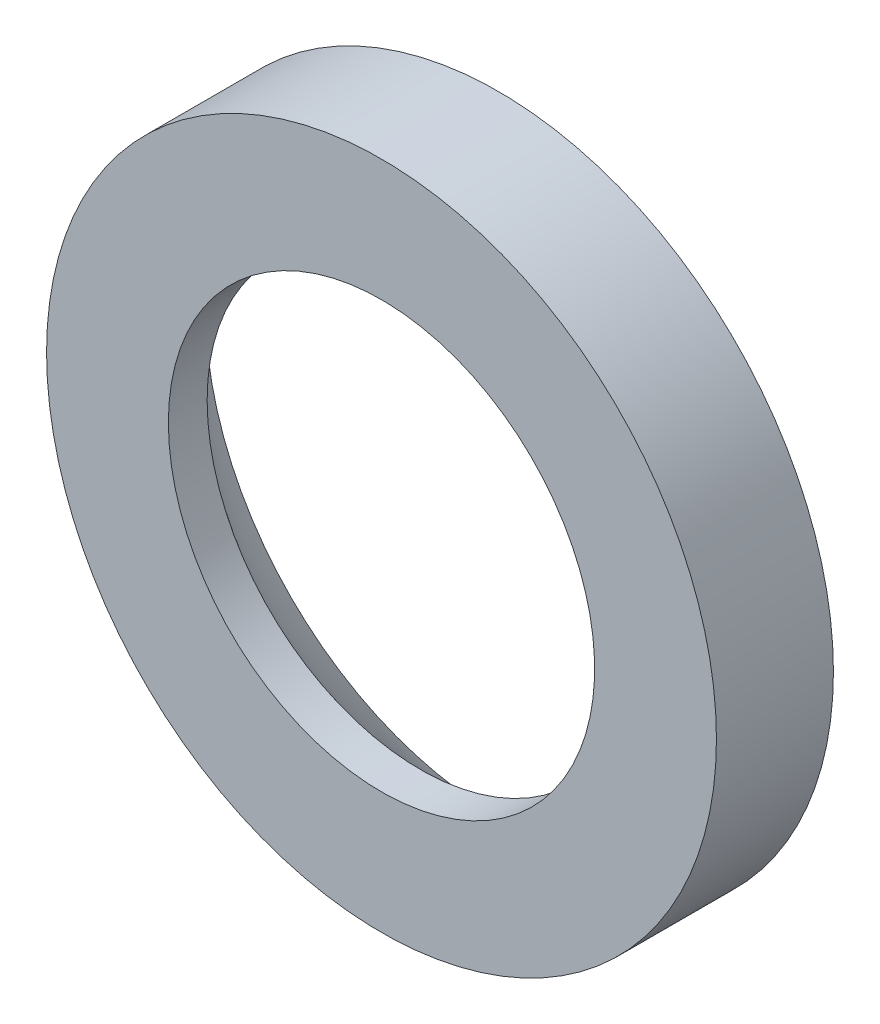
SolidWorks part; units mm, degrees
ref_plane "Front Plane" through (0, 0, 0) normal (0, 0, 1) x (1, 0, 0)
ref_plane "Top Plane" through (0, 0, 0) normal (0, 1, 0) x (1, 0, 0)
ref_plane "Right Plane" through (0, 0, 0) normal (1, 0, 0) x (0, 0, -1)
sketch3d "Plane points - Printable flat rim and spherical seat"
  point P0 (0, 0, 0)
  point P1 (0, 18, 0)
  point P2 (0, 0, 18)
ref_plane "Drilling plane - Printable flat rim and spherical seat" through (0, 0, 0) normal (1, 0, 0) x (0, 0, -1)
sketch "S01 - Printable flat rim and spherical seat" plane through (0, 0, 0) normal (1, 0, 0) x (0, 0, -1)
  line L0 (15, 0) -> (-15, 0) construction
  line L1 (-4.2, 2.66) -> (-4.2, 4.18)
  line L2 (-4.2, 4.18) -> (-2.74, 4.18)
  line L3 (-2.74, 4.18) -> (-2.74, 3.6575)
  line L4 (-3.7161, 2.66) -> (-4.2, 2.66)
  arc A0 (-2.74, 3.6575) -> (-3.7161, 2.66) centre (0, 0) ccw
revolve "01 - Printable flat rim and spherical seat" add sketch "S01 - Printable flat rim and spherical seat" angle 360 about L0
